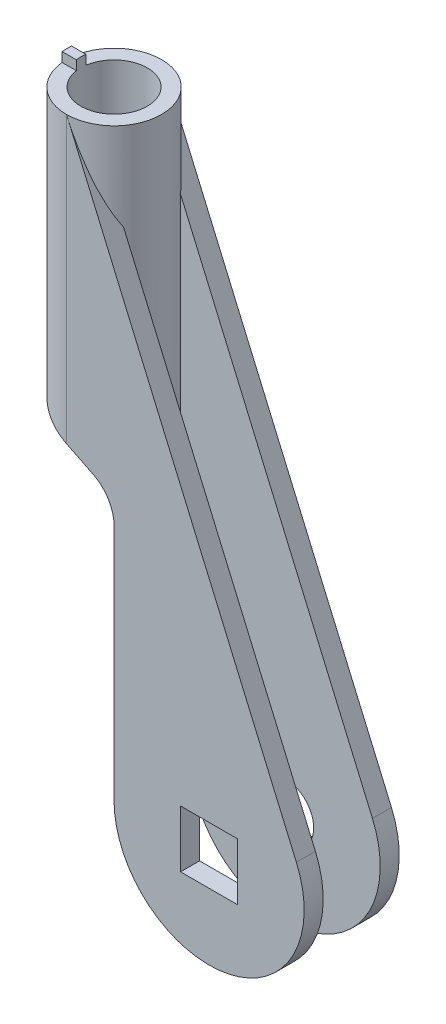
SolidWorks part; units mm, degrees
material "Copper"
ref_plane "Front Plane" through (0, 0, 0) normal (0, 0, 1) x (1, 0, 0)
ref_plane "Top Plane" through (0, 0, 0) normal (0, 1, 0) x (1, 0, 0)
ref_plane "Right Plane" through (0, 0, 0) normal (1, 0, 0) x (0, 0, -1)
sketch "Sketch1" plane through (0, 0, 0) normal (0, 0, 1) x (1, 0, 0)
  line L0 (10, 0) -> (10, 25)
  line L1 (10, 25) -> (10, 25.0279)
  line L2 (15, 30) -> (15, 60)
  line L3 (12.2111, 28.6056) -> (15, 30)
  line L4 (-9.1816, 3.9621) -> (15, 60)
  arc A0 (-9.1816, 3.9621) -> (10, 0) centre (0, 0) ccw
  arc A1 (10, 25.0279) -> (12.2111, 28.6056) centre (14, 25.0279) cw
  circle A2 centre (0, 0) radius 3
  dimension "D1" = 4
extrude "Boss-Extrude1" add sketch "Sketch1" along normal blind 2
ref_plane "Plane1" through (0, 0, 8) normal (0, 0, 1) x (1, 0, 0)
sketch "Sketch2" plane through (0, 0, 8) normal (0, 0, 1) x (1, 0, 0)
  line L0 (10, 0) -> (10, 25.0279)
  line L1 (10, 25.0279) -> (10, 25.0434)
  line L2 (12.2271, 28.629) -> (15, 30)
  line L3 (15, 30) -> (15, 60)
  line L4 (15, 60) -> (-9.1816, 3.9621)
  circle A0 centre (0, 0) radius 3
  arc A1 (-9.1816, 3.9621) -> (10, 0) centre (0, 0) ccw
  arc A2 (10, 25.0434) -> (12.2271, 28.629) centre (14, 25.0434) cw
  dimension "D1" = 4
extrude "Boss-Extrude2" add sketch "Sketch2" along normal blind 2 separate body
ref_plane "Plane2" through (0, 60, 0) normal (0, 1, 0) x (1, 0, 0)
sketch "Sketch3" plane through (0, 60, 0) normal (0, 1, 0) x (1, 0, 0)
  line L0 (15, -2) -> (15, -8)
  line L1 (-13.75, -8) -> (13.75, -8) construction
  circle A2 centre (15, -5) radius 5
  dimension "D1" = 10
extrude "Cut-Extrude1" cut sketch "Sketch3" against normal blind 38
sketch "Sketch4" plane through (0, 60, 0) normal (0, 1, 0) x (1, 0, 0)
  line L0 (15, -10) -> (15, 0)
  line L1 (-13.75, 0) -> (13.75, 0) construction
  circle A0 centre (15, -5) radius 5
  dimension "D1" = 10
extrude "Boss-Extrude3" add sketch "Sketch4" against normal blind 35 contours L0 A0 | L0 A0
sketch "Sketch5" plane through (0, 0, 0) normal (0, 0, 1) x (1, 0, 0)
  line L0 (10, 25.0279) -> (10, 25.0434)
  line L1 (12.2271, 28.629) -> (15, 30)
  line L2 (15, 30) -> (20, 32.4721)
  line L3 (20, 25) -> (20, 60) construction
  line L4 (20, 32.4721) -> (20, 25)
  line L5 (20, 25) -> (20, 22.6312)
  line L6 (20, 22.6312) -> (10, 22.6312)
  line L7 (10, 0) -> (10, 25.0279) construction
  line L8 (10, 22.6312) -> (10, 25.0279)
  arc A0 (10, 25.0434) -> (12.2271, 28.629) centre (14, 25.0434) cw
  dimension "D1" = 4
extrude "Cut-Extrude2" cut sketch "Sketch5" along normal blind 13
sketch "Sketch6" plane through (0, 60, 0) normal (0, 1, 0) x (1, 0, 0)
  circle A0 centre (15, -5) radius 3.5
extrude "Cut-Extrude3" cut sketch "Sketch6" against normal blind 42
sketch "Sketch7" plane through (0, 0, 0) normal (0, 0, -1) x (-1, 0, 0)
  line L1 (-3, 3) -> (3, 3)
  line L2 (-3, 3) -> (-3, -3)
  line L3 (-3, -3) -> (3, -3)
  line L4 (3, 3) -> (3, -3)
  line L5 (-3, 3) -> (3, -3) construction
  line L6 (-3, -3) -> (3, 3) construction
  point P0 (0, 0)
extrude "Cut-Extrude4" cut sketch "Sketch7" against normal blind 5
move or copy body "Body-Move/Copy1" bodies to move or copy 109 copy no rotation origin (5, 0, 5) rotation axis (0, 1, 0) rotation angle 90
move or copy body "Body-Move/Copy2" bodies to move or copy 110 copy no rotation origin (5, 0, 5) rotation axis (0, 1, 0) rotation angle 45
move or copy body "Body-Move/Copy3" bodies to move or copy 111 copy no rotation origin (6.0355, 0, 6.0355) rotation axis (0, 1, 0) rotation angle 45
sketch "Sketch8" plane through (0, 0, 0) normal (1, 0, 0) x (0, 0, -1)
  line L1 (-9.0355, 50.7305) -> (-9.0355, 3.9621) construction
  line L2 (-3.0355, 50.7305) -> (-3.0355, 3.9621) construction
  line L3 (-3.0355, 27.3463) -> (-5.864, 30.1747)
  line L4 (-5.864, 30.1747) -> (-9.0355, 27.3463)
  line L5 (-9.0355, 27.3463) -> (-6.0355, 25.0434)
  line L6 (-6.0355, 25.0434) -> (-3.0355, 27.3463)
extrude "Cut-Extrude5" cut sketch "Sketch8" against normal blind 10
sketch "Sketch10" plane through (0, 60, 0) normal (0, 1, 0) x (1, 0, 0)
  line L0 (-5.4289, -2.5355) -> (-5.4289, -1.0355)
  circle A0 centre (-5.4289, -6.0355) radius 3.5 construction
sketch "Sketch11" plane through (0, 60, 0) normal (0, 1, 0) x (1, 0, 0)
  line L0 (-10.4039, -6.5355) -> (-10.4039, -5.5355)
  line L1 (-10.4039, -6.5355) -> (-8.893, -6.5355)
  line L2 (-10.4039, -5.5355) -> (-8.893, -5.5355)
  arc A0 (-8.893, -5.5355) -> (-8.893, -6.5355) centre (-5.4289, -6.0355) ccw
  arc A1 (-10.4039, -5.5355) -> (-10.4039, -6.5355) centre (-5.4289, -6.0355) ccw
  circle M4 centre (-5.4289, -6.0355) radius 3.5
extrude "Boss-Extrude4" add sketch "Sketch11" along normal blind 1 contours L2 L0 L1 M4
